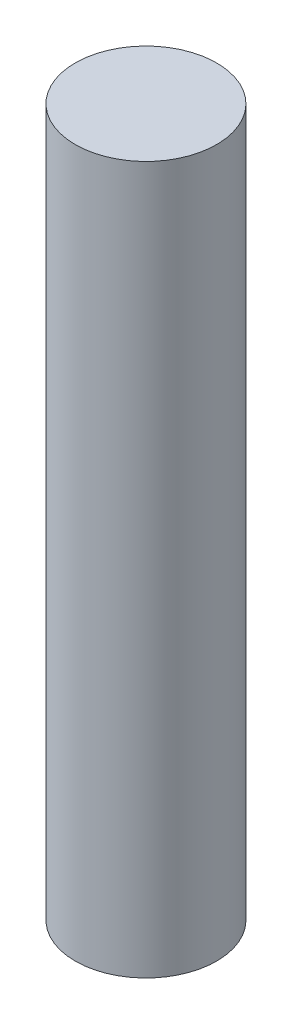
SolidWorks part; units mm, degrees
material "AISI 1020"
ref_plane "Front Plane" through (0, 0, 0) normal (0, 0, 1) x (1, 0, 0)
ref_plane "Top Plane" through (0, 0, 0) normal (0, 1, 0) x (1, 0, 0)
ref_plane "Right Plane" through (0, 0, 0) normal (1, 0, 0) x (0, 0, -1)
sketch "Sketch1" plane through (0, 0, 0) normal (0, 1, 0) x (1, 0, 0)
  circle A0 centre (0, 0) radius 1
  dimension "D1" = 2
extrude "Boss-Extrude1" add sketch "Sketch1" along normal blind 10
equation "\"bearing OD\" = 20mm"
equation "\"bearing outer race thickness\"= 1mm"
equation "\"bearing ID\"= 10mm"
equation "\"bearing depth\"= 6mm"
equation "\"bearing inner race thickness\"= 1mm"
equation "\"seal OD\" = 20mm"
equation "\"seal ID\"= 8mm"
equation "\"seal depth\"= 6mm"
equation "\"impeller dowel diameter\" = 2mm"
equation "\"impeller dowel length\" = 2mm*2 + \"coupler shaft impeller section diameter\""
equation "\"impeller base outer diameter\"= 1.75in"
equation "\"impeller base outer thickness\"= 1mm"
equation "\"impeller base center thickness\"= 5mm"
equation "\"impeller number of vanes\"= 8"
equation "\"impeller vane outer height\"= 4mm"
equation "\"impeller vane inner height\"= 8mm"
equation "\"impeller primary vane opening diamater\"= 10mm"
equation "\"impeller vane inner thickness\"= .75mm"
equation "\"impeller vane outer thickness\"= 1.5mm"
equation "\"impeller primary vane entrance angle\"= 20deg"
equation "\"impeller secondary vane entrance angle\"= 20deg"
equation "\"impeller secondary vane opening diameter\"= 10mm"
equation "\"impeller bolt surface height\" = 5mm"
equation "\"impeller bolt surface diameter\" = 8mm"
equation "\"impeller dowel hole\"= 2mm"
equation "\"motor to housing distance\"= 60mm"
equation "\"motor mount pattern diameter\"= 30mm"
equation "\"motor mount coupler shaft hole diameter\"= \"coupler shaft base diameter\"+ 4mm"
equation "\"motor mount to housing m8 screw hole diameter\"= 8.5mm"
equation "\"motor mount to housing m8 screw post radius\"= ( 3 * \"motor mount to housing m8 screw hole diameter\" ) / 2"
equation "\"motor mount to housing m8 pattern diameter\"= 100mm"
equation "\"motor mount to housing m4 screw hole diamater\"= 4mm"
equation "\"motor mount to housing m4 head diameter\"= 7.25mm"
equation "\"motor mount to housing m4 head depth\"= 4mm"
equation "\"motor mount plate thickness\"= 6mm + \"motor mount to housing m4 head depth\""
equation "\"housing bearing seat lip thickness\" = 2mm"
equation "\"housing base thickness\"= \"housing bearing seat lip thickness\" + \"seal depth\" + \"bearing depth\""
equation "\"housing top impeller vertical clearance\"= .5mm"
equation "\"housing top impeller horizontal clearance\"= .5mm"
equation "\"housing top impeller bottom clearance\"= 1mm"
equation "\"housing top impeller cavity height\"= \"housing top impeller bottom clearance\" + \"impeller base center thickness\" + \"impeller vane inner height\" + \"housing top impeller vertical clearance\""
equation "\"housing top impeller cavity diameter\"= 2 * \"housing top impeller horizontal clearance\" + \"impeller base outer diameter\""
equation "\"housing top impeller cavity tip height\"= \"housing top impeller bottom clearance\" + \"housing top impeller vertical clearance\" + \"impeller base outer thickness\" + \"impeller vane outer height\""
equation "\"housing top entrance OD\"= 20mm"
equation "\"housing top exit OD\"= 5mm"
equation "\"housing top o-ring channel height\"= 1.5mm"
equation "\"housing top o ring channel width\"= 1.5mm"
equation "\"housing top o-ring circumference\" = 250mm"
equation "\"housing top o-ring radius\" = (\"housing top o-ring circumference\")/(2*3.14)"
equation "\"housing top threaded inlet depth\"= 8mm"
equation "\"housing top total thickness\"= \"housing top threaded inlet depth\" + \"housing top impeller cavity height\""
equation "\"housing top total width\"= 10mm"
equation "\"housing top exit threaded diameter\"= 8mm"
equation "\"housing top exit threaded depth\"= 8mm"
equation "\"motor shaft pride\"= 32mm"
equation "\"motor shaft flat section length from tip\"= 25.7mm"
equation "\"motor shaft bore end clearance\"= 2mm"
equation "\"coupler shaft to motor clearance\" = 2mm"
equation "\"motor mount shaft hole depth\"= \"motor shaft pride\""
equation "\"coupler shaft set screw drill hole diameter\"= 6mm"
equation "\"coupler shaft set screw 1 distance\"= \"motor mount shaft hole depth\" / 3"
equation "\"coupler shaft set screw 2 distance\"= \"motor mount shaft hole depth\" * 4 / 5"
equation "\"coupler shaft motor shaft hole diameter\"= 8mm"
equation "\"coupler shaft base diameter\"= 18mm"
equation "\"coupler shaft base length\"= \"motor mount shaft hole depth\" + 10mm"
equation "\"coupler shaft second section diameter\"= \"bearing ID\" + \"bearing inner race thickness\" * 2"
equation "\"coupler shaft second section length\"= \"motor to housing distance\" -  \"coupler shaft base length\" - 2mm"
equation "\"coupler shaft third section diamater\"= \"bearing ID\""
equation "\"coupler shaft third section length\"= \"bearing depth\""
equation "\"coupler shaft seal section diameter\" = \"seal ID\""
equation "\"coupler shaft seal section length\" = \"housing base thickness\"+\"housing top impeller bottom clearance\"-\"bearing depth\""
equation "\"coupler shaft impeller section diameter\" = 6mm"
equation "\"coupler shaft impeller section length\" = \"impeller boss depth\"+\"impeller base center thickness\" - 1mm"
equation "\"coupler shaft impeller screw hole diameter\" = \"motor mount to housing m4 screw hole diamater\""
equation "\"coupler shaft impeller screw hole depth\" = 10mm"
equation "\"coupler shaft impeller dowel hole\"= \"impeller dowel length\"-2mm"
equation "\"D1@Sketch1\"=\"impeller dowel diameter\""
equation "\"D1@Boss-Extrude1\"=\"impeller dowel length\" "
